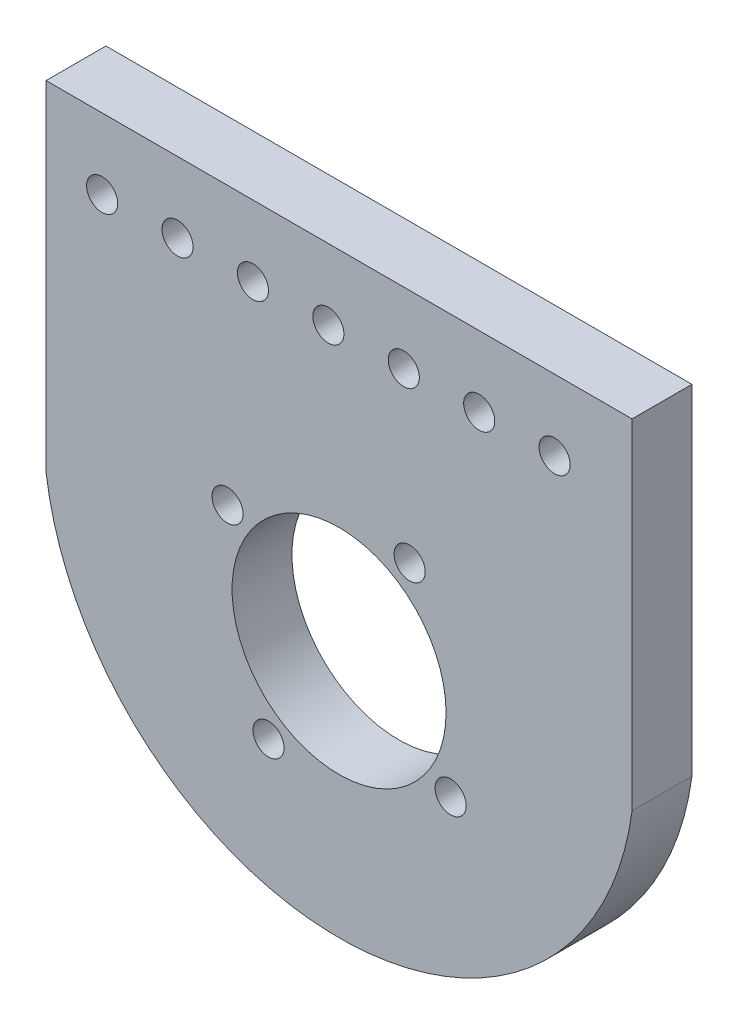
SolidWorks part; units mm, degrees
ref_plane "Front" through (0, 0, 0) normal (0, 0, 1) x (1, 0, 0)
ref_plane "Top" through (0, 0, 0) normal (0, 1, 0) x (1, 0, 0)
ref_plane "Right" through (0, 0, 0) normal (1, 0, 0) x (0, 0, -1)
sketch "Sketch1" plane through (0, 0, 0) normal (0, 0, 1) x (1, 0, 0)
  line L0 (-31.0822, 36.8639) -> (31.0822, 36.8639)
  line L1 (-31.0822, 36.8639) -> (-31.0822, 0.8639)
  line L2 (31.0822, 36.8639) -> (31.0822, 0.8639)
  line L3 (-31.0822, 29.3639) -> (31.0822, 29.3639) construction
  line L10 (-15.0822, 29.3639) -> (47.0822, 29.3639) construction
  line L11 (-7.0822, 29.3639) -> (55.0822, 29.3639) construction
  line L12 (0.9178, 29.3639) -> (63.0822, 29.3639) construction
  line L13 (8.9178, 29.3639) -> (71.0822, 29.3639) construction
  line L14 (16.9178, 29.3639) -> (79.0822, 29.3639) construction
  line L15 (-23.0822, 29.3639) -> (39.0822, 29.3639) construction
  circle A0 centre (0, 0) radius 11.35
  arc A1 (-31.0822, 0.8639) -> (31.0822, 0.8639) centre (0, 5) ccw
  circle A2 centre (0, 0) radius 14 construction
  circle A3 centre (-11.832, 7.4835) radius 1.65
  circle A4 centre (7.4835, 11.832) radius 1.65
  circle A5 centre (11.832, -7.4835) radius 1.65
  circle A6 centre (-7.4835, -11.832) radius 1.65
  circle A7 centre (-25.1356, 29.3639) radius 1.65
  circle A8 centre (-17.1356, 29.3639) radius 1.65
  circle A9 centre (-9.1356, 29.3639) radius 1.65
  circle A10 centre (-1.1356, 29.3639) radius 1.65
  circle A11 centre (6.8644, 29.3639) radius 1.65
  circle A12 centre (14.8644, 29.3639) radius 1.65
  circle A13 centre (22.8644, 29.3639) radius 1.65
  point P6 (0, 36.8639)
  point P21 (0, 0)
  dimension "D1" = 22.7
  dimension "D2" = 28
  dimension "D3" = 3.3
  dimension "D5" = 5
  dimension "D9" = 3.3
  dimension "D7" = 36
  dimension "D8" = 7.5
  dimension "D11" = 8
  dimension "D10" = 7
  dimension "D4" = 4
extrude "Boss-Extrude1" add sketch "Sketch1" along normal blind 6.35
